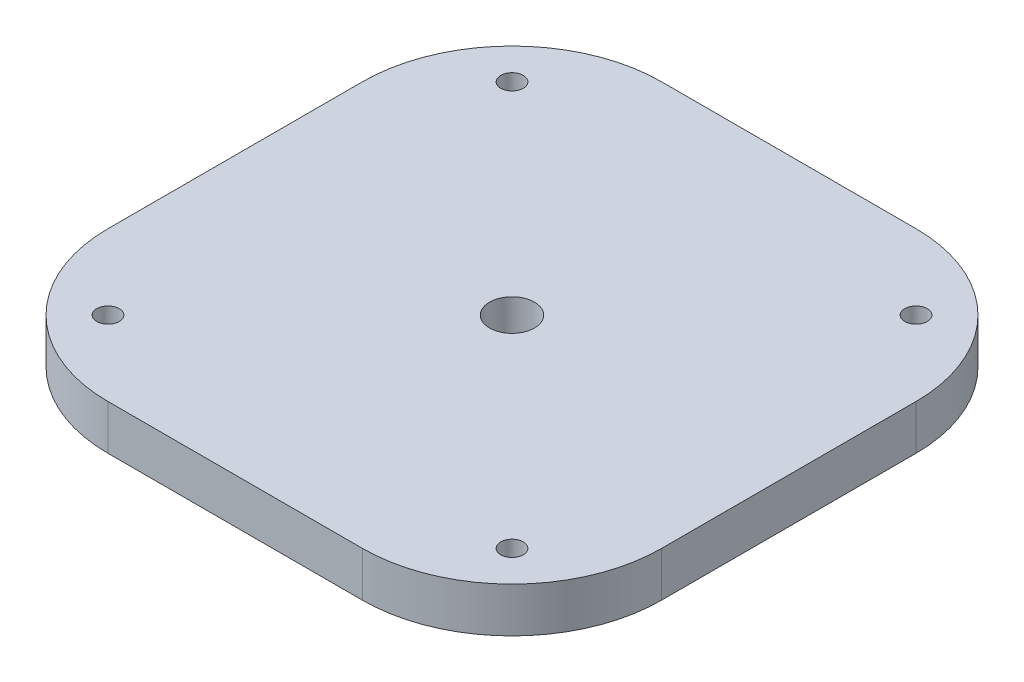
SolidWorks part; units mm, degrees
material "ABS"
ref_plane "Спереди" through (0, 0, 0) normal (0, 0, 1) x (1, 0, 0)
ref_plane "Сверху" through (0, 0, 0) normal (0, 1, 0) x (1, 0, 0)
ref_plane "Справа" through (0, 0, 0) normal (1, 0, 0) x (0, 0, -1)
sketch "Эскиз1" plane through (0, 0, 0) normal (0, 1, 0) x (1, 0, 0)
  line L1 (17, -37) -> (-17, -37)
  line L2 (37, -17) -> (37, 17)
  line L3 (17, 37) -> (-17, 37)
  line L4 (-37, -17) -> (-37, 17)
  line L5 (37, -37) -> (-37, 37) construction
  line L6 (37, 37) -> (-37, -37) construction
  arc A0 (37, 17) -> (17, 37) centre (17, 17) ccw
  arc A1 (17, -37) -> (37, -17) centre (17, -17) ccw
  arc A2 (-17, -37) -> (-37, -17) centre (-17, -17) cw
  arc A3 (-17, 37) -> (-37, 17) centre (-17, 17) ccw
  point P0 (0, 0)
  dimension "D3" = 20
  dimension "D1" = 74
  dimension "D2" = 74
extrude "Бобышка-Вытянуть1" add sketch "Эскиз1" along normal blind 6
sketch "Эскиз2" plane through (0, 0, 0) normal (0, 1, 0) x (1, 0, 0)
  line L1 (27, -27) -> (-27, -27)
  line L2 (27, -27) -> (27, 27)
  line L3 (27, 27) -> (-27, 27)
  line L4 (-27, -27) -> (-27, 27)
  line L5 (27, -27) -> (-27, 27) construction
  line L6 (27, 27) -> (-27, -27) construction
  circle A0 centre (-27, 27) radius 1.5
  circle A1 centre (27, 27) radius 1.5
  circle A2 centre (27, -27) radius 1.5
  circle A3 centre (-27, -27) radius 1.5
  circle A4 centre (0, 0) radius 3
  point P0 (0, 0)
  dimension "D1" = 3
  dimension "D4" = 6
  dimension "D2" = 54
  dimension "D3" = 54
extrude "Вырез-Вытянуть1" cut sketch "Эскиз2" along normal blind 6 contours A0 | A1 | A2 | A3 | A4
sketch "Эскиз3" plane through (0, 0, 0) normal (0, 1, 0) x (1, 0, 0)
  line L1 (-28.7321, 30) -> (-30.4641, 27)
  line L2 (-30.4641, 27) -> (-28.7321, 24)
  line L3 (-28.7321, 24) -> (-25.2679, 24)
  line L4 (-25.2679, 24) -> (-23.5359, 27)
  line L5 (-23.5359, 27) -> (-25.2679, 30)
  line L6 (-25.2679, 30) -> (-28.7321, 30)
  line L7 (25.2679, 30) -> (23.5359, 27)
  line L8 (23.5359, 27) -> (25.2679, 24)
  line L9 (25.2679, 24) -> (28.7321, 24)
  line L10 (28.7321, 24) -> (30.4641, 27)
  line L11 (30.4641, 27) -> (28.7321, 30)
  line L12 (28.7321, 30) -> (25.2679, 30)
  line L13 (25.2679, -24) -> (23.5359, -27)
  line L14 (23.5359, -27) -> (25.2679, -30)
  line L15 (25.2679, -30) -> (28.7321, -30)
  line L16 (28.7321, -30) -> (30.4641, -27)
  line L17 (30.4641, -27) -> (28.7321, -24)
  line L18 (28.7321, -24) -> (25.2679, -24)
  line L19 (-28.7321, -24) -> (-30.4641, -27)
  line L20 (-30.4641, -27) -> (-28.7321, -30)
  line L21 (-28.7321, -30) -> (-25.2679, -30)
  line L22 (-25.2679, -30) -> (-23.5359, -27)
  line L23 (-23.5359, -27) -> (-25.2679, -24)
  line L24 (-25.2679, -24) -> (-28.7321, -24)
  circle A0 centre (-27, 27) radius 3 construction
  circle A1 centre (27, 27) radius 3 construction
  circle A2 centre (27, -27) radius 3 construction
  circle A3 centre (-27, -27) radius 3 construction
  dimension "6" = 6
extrude "Вырез-Вытянуть2" cut sketch "Эскиз3" along normal blind 2
sketch "Эскиз4" plane through (0, 0, 0) normal (0, 1, 0) x (1, 0, 0)
  arc A0 (-37, -17) -> (-17, -37) centre (-17, -17) ccw construction
  arc A1 (17, -37) -> (37, -17) centre (17, -17) ccw construction
  arc A2 (37, 17) -> (17, 37) centre (17, 17) ccw construction
  arc A3 (-17, 37) -> (-37, 17) centre (-17, 17) ccw construction
  arc A4 (-37, -17) -> (-17, -37) centre (-17, -17) ccw
  arc A5 (17, -37) -> (37, -17) centre (17, -17) ccw
  arc A6 (37, 17) -> (17, 37) centre (17, 17) ccw
  arc A7 (-17, 37) -> (-37, 17) centre (-17, 17) ccw
  circle A8 centre (0, 67.5941) radius 35
  circle A9 centre (67.5941, 0.9713) radius 35
  circle A10 centre (0.9713, -66.6228) radius 35
  circle A11 centre (-66.6228, 0) radius 35
  point P23 (0.4857, 0.4857)
  dimension "D1" = 70
  dimension "D2" = 4
extrude "Вырез-Вытянуть3" [suppressed] cut sketch "Эскиз4" along normal through all contours A11 | A8 | A9 | A10
equation "\"D2@Эскиз1\"=\"D1@Эскиз1\""
equation "\"D3@Эскиз2\"=\"D2@Эскиз2\""
